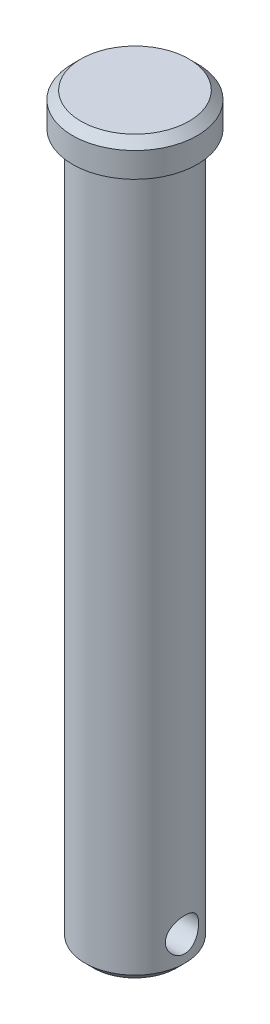
SolidWorks part; units mm, degrees
material "C40 or 38NiCrMo4"
ref_plane "Piano frontale" through (0, 0, 0) normal (0, 0, 1) x (1, 0, 0)
ref_plane "Piano superiore" through (0, 0, 0) normal (0, 1, 0) x (1, 0, 0)
ref_plane "Piano destro" through (0, 0, 0) normal (1, 0, 0) x (0, 0, -1)
sketch "Sketch1" plane through (0, 0, 0) normal (0, 1, 0) x (1, 0, 0)
  circle A0 centre (0, 0) radius 15
  dimension "D1" = 30
extrude "Extrude1" add sketch "Sketch1" along normal blind 8
sketch "Sketch2" plane through (0, 0, 0) normal (0, -1, 0) x (1, 0, 0)
  circle A0 centre (0, 0) radius 12
  dimension "D1" = 24
extrude "Extrude2" add sketch "Sketch2" along normal blind 170
sketch "Sketch3" plane through (0, 0, 0) normal (1, 0, 0) x (0, 0, -1)
  line L0 (0, -1000) -> (0, 49000) construction
  circle A0 centre (0, -162) radius 4
  dimension "D1" = 8
  dimension "D2" = 162
extrude "Extrude3" cut sketch "Sketch3" against normal through all and the other way through all
chamfer "Chamfer1" distance 2 angle 45 2 edges at (0, -170, -12) (0, 8, 15)
